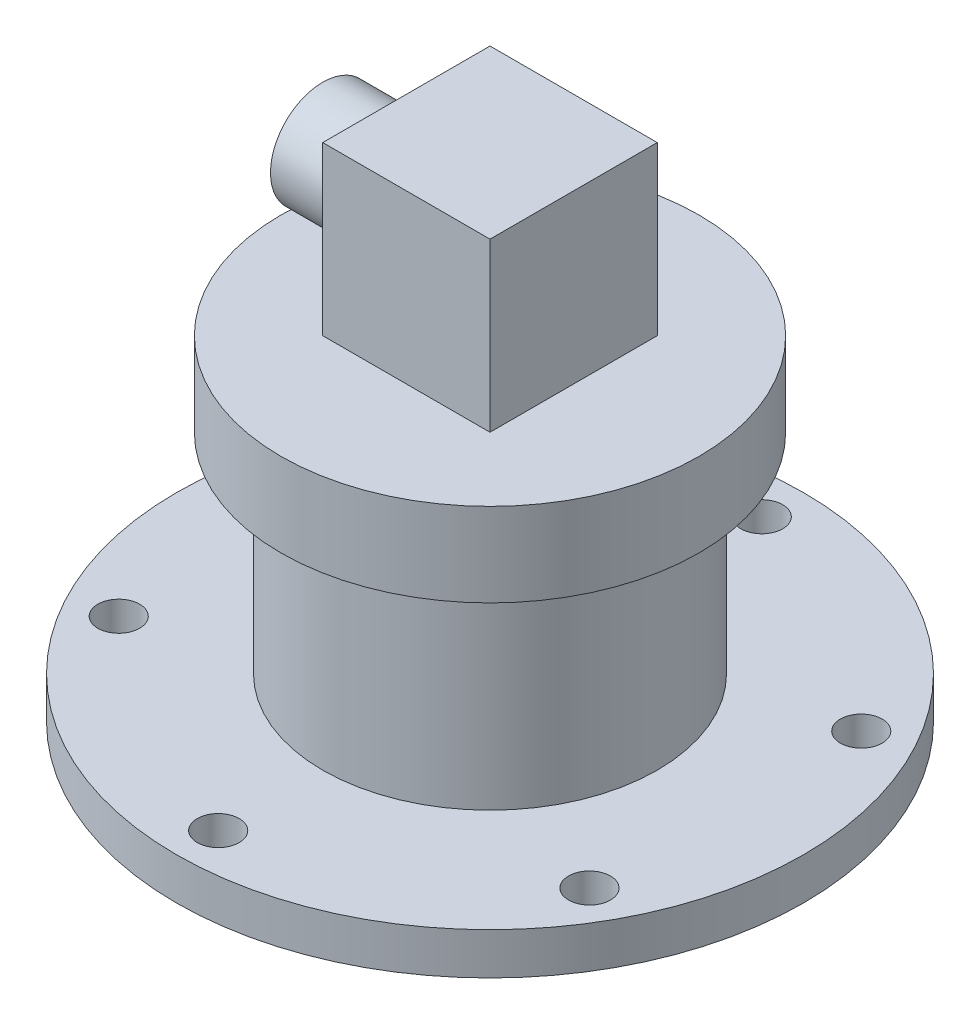
SolidWorks part; units mm, degrees
ref_plane "Front Plane" through (0, 0, 0) normal (0, 0, 1) x (1, 0, 0)
ref_plane "Top Plane" through (0, 0, 0) normal (0, 1, 0) x (1, 0, 0)
ref_plane "Right Plane" through (0, 0, 0) normal (1, 0, 0) x (0, 0, -1)
sketch "Sketch1" plane through (0, 0, 0) normal (0, 1, 0) x (1, 0, 0)
  circle A0 centre (0, 0) radius 75
  dimension "D1" = 150
extrude "Boss-Extrude1" add sketch "Sketch1" along normal blind 10
sketch "Sketch2" plane through (0, 10, 0) normal (0, 1, 0) x (1, 0, 0)
  circle A0 centre (0, 65) radius 5
  circle A1 centre (56.2917, 32.5) radius 5
  circle A2 centre (56.2917, -32.5) radius 5
  circle A3 centre (0, -65) radius 5
  circle A4 centre (-56.2917, -32.5) radius 5
  circle A5 centre (-56.2917, 32.5) radius 5
  point P15 (0, 0)
  dimension "D1" = 10
  dimension "D2" = 65
  dimension "D3" = 6
extrude "Cut-Extrude1" cut sketch "Sketch2" against normal blind 10
sketch "Sketch3" plane through (0, 10, 0) normal (0, 1, 0) x (1, 0, 0)
  circle A0 centre (0, 0) radius 40
  dimension "D1" = 80
extrude "Boss-Extrude2" add sketch "Sketch3" along normal blind 50
sketch "Sketch4" plane through (0, 60, 0) normal (0, 1, 0) x (1, 0, 0)
  circle A0 centre (0, 0) radius 50
  dimension "D1" = 100
extrude "Boss-Extrude3" add sketch "Sketch4" along normal blind 20
sketch "Sketch5" plane through (0, 80, 0) normal (0, 1, 0) x (1, 0, 0)
  line L1 (-20, 20) -> (20, 20)
  line L2 (-20, 20) -> (-20, -20)
  line L3 (-20, -20) -> (20, -20)
  line L4 (20, 20) -> (20, -20)
  line L5 (-20, 20) -> (20, -20) construction
  line L6 (-20, -20) -> (20, 20) construction
  point P0 (0, 0)
  dimension "D1" = 40
  dimension "D2" = 40
extrude "Boss-Extrude4" add sketch "Sketch5" along normal blind 40
sketch "Sketch6" plane through (-20, 0, 0) normal (-1, 0, 0) x (0, 0, 1)
  line L0 (-20, 120) -> (20, 120) construction
  line L1 (-20, 120) -> (-20, 80) construction
  circle A0 centre (0, 100) radius 12.5
  point P6 (-122.4704, 121.8224)
  dimension "D1" = 25
  dimension "D2" = 20
  dimension "D3" = 20
extrude "Boss-Extrude5" add sketch "Sketch6" along normal blind 20
sketch "Sketch9" plane through (-40, 0, 0) normal (-1, 0, 0) x (0, 0, 1)
  circle A0 centre (0, 100) radius 7.5
  dimension "D1" = 15
extrude "Cut-Extrude2" cut sketch "Sketch9" against normal blind 15
